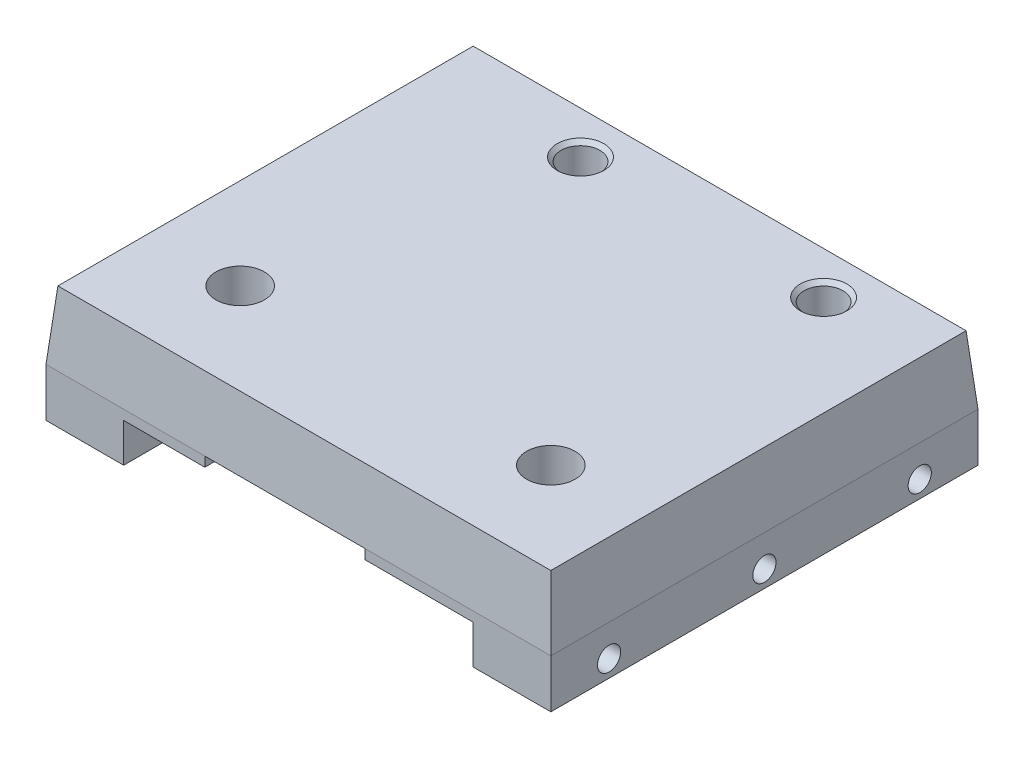
SolidWorks part; units mm, degrees
material "6061 Alloy"
ref_plane "Front Plane" through (0, 0, 0) normal (0, 0, 1) x (1, 0, 0)
ref_plane "Top Plane" through (0, 0, 0) normal (0, 1, 0) x (1, 0, 0)
ref_plane "Right Plane" through (0, 0, 0) normal (1, 0, 0) x (0, 0, -1)
sketch "Sketch1" plane through (0, 0, 0) normal (0, 1, 0) x (1, 0, 0)
  line L1 (41.275, -34.925) -> (-41.275, -34.925)
  line L2 (41.275, -34.925) -> (41.275, 34.925)
  line L3 (41.275, 34.925) -> (-41.275, 34.925)
  line L4 (-41.275, -34.925) -> (-41.275, 34.925)
  line L5 (41.275, -34.925) -> (-41.275, 34.925) construction
  line L6 (41.275, 34.925) -> (-41.275, -34.925) construction
  line L7 (-22.225, 34.925) -> (28.575, 34.925)
  line L8 (-22.225, 34.925) -> (-22.225, 92.075)
  line L9 (-22.225, 92.075) -> (28.575, 92.075)
  line L10 (28.575, 34.925) -> (28.575, 92.075)
  point P0 (0, 0)
  dimension "D1" = 82.55
  dimension "D2" = 69.85
  dimension "D3" = 12.7
  dimension "D4" = 19.05
  dimension "D5" = 50.8
  dimension "D6" = 127
extrude "Boss-Extrude1" add sketch "Sketch1" along normal blind 7.9375 contours L4 L1 L2 L3
sketch "Sketch2" plane through (0, 7.9375, 0) normal (0, 1, 0) x (1, 0, 0)
  line L1 (-41.275, -34.925) -> (41.275, -34.925)
  line L2 (-41.275, -34.925) -> (-41.275, 34.925)
  line L3 (-41.275, 34.925) -> (41.275, 34.925)
  line L4 (41.275, -34.925) -> (41.275, 34.925)
extrude "Boss-Extrude2" add sketch "Sketch2" along normal blind 3.175
hole_wizard "3/8-16 Tapped Hole1" positions "Sketch10" profile "Sketch11" tap size "3/8-16" standard "ANSI Inch"
sketch "Sketch10" plane through (0, 11.1125, 0) normal (0, 1, 0) x (1, 0, 0)
  line L0 (-41.275, 34.925) -> (-41.275, -34.925) construction
  line L1 (-41.275, -34.925) -> (41.275, -34.925) construction
  line L2 (41.275, -34.925) -> (41.275, 34.925) construction
  point P0 (-25.4, -19.05)
  point P2 (25.4, -19.05)
  dimension "D1" = 15.875
  dimension "D2" = 15.875
  dimension "D3" = 15.875
  dimension "D4" = 15.875
sketch "Sketch11" plane through (-25.4, 11.1125, 19.05) normal (1, 0, 0) x (0, 0, 1)
  line L0 (0, 0) -> (0, 11.9097)
  line L1 (0, 11.9097) -> (3.9687, 9.525)
  line L2 (3.9687, 9.525) -> (3.9687, 0)
  line L5 (3.9687, 0) -> (0, 0)
  line L10 (0, 11.9097) -> (-3.9688, 9.525) construction
  line L11 (0, -6.35) -> (0, 107.95) construction
  dimension "Tap Drill Dia." = 7.9375
  dimension "Tap Drill Depth" = 9.525
  dimension "Drill Angle" = 118
cosmetic thread "Hole Thread4" parameters "D1"=19.05, "D2"=9.525
cosmetic thread "Hole Thread5" parameters "D1"=19.05, "D2"=9.525
draft "Draft1" type of draft neutral plane draft angle 5 neutral plane "Top Plane" faces to draft 4 face at (0, 5.5563, -34.925) face at (-41.275, 5.5563, 0) face at (0, 5.5563, 34.925) face at (41.275, 5.5563, 0) neutral plane through (0, 0, 0) neutral plane normal (0, 1, 0) parameters "D1"=5
sketch "Sketch3" plane through (0, 0, 0) normal (0, -1, 0) x (1, 0, 0)
  line L7 (41.275, 34.925) -> (28.575, 34.925)
  line L8 (41.275, 34.925) -> (41.275, -34.925)
  line L9 (41.275, -34.925) -> (28.575, -34.925)
  line L10 (28.575, 34.925) -> (28.575, -34.925)
  line L13 (-41.275, -34.925) -> (-28.575, -34.925)
  line L14 (-41.275, -34.925) -> (-41.275, 34.925)
  line L15 (-41.275, 34.925) -> (-28.575, 34.925)
  line L16 (-28.575, -34.925) -> (-28.575, 34.925)
  dimension "D1" = 12.7
  dimension "D2" = 12.7
extrude "Boss-Extrude3" add sketch "Sketch3" along normal blind 7.9375
sketch "Sketch4" plane through (0, 0, 0) normal (0, -1, 0) x (1, 0, 0)
  line L1 (-28.575, 34.925) -> (-15.3077, 34.925)
  line L2 (-28.575, 34.925) -> (-28.575, -34.925)
  line L3 (-28.575, -34.925) -> (-15.3077, -34.925)
  line L4 (-15.3077, 34.925) -> (-15.3077, -34.925)
  line L6 (28.575, 34.925) -> (10.8909, 34.925)
  line L7 (28.575, 34.925) -> (28.575, -34.925)
  line L8 (28.575, -34.925) -> (10.8909, -34.925)
  line L9 (10.8909, 34.925) -> (10.8909, -34.925)
extrude "Wear Pads" add sketch "Sketch4" along normal blind 1.5875
hole_wizard "#10-24 Tapped Hole1" positions "Sketch5" profile "Sketch6" tap size "#10-24" standard "ANSI Inch"
sketch "Sketch5" plane through (41.275, 0, 0) normal (1, 0, 0) x (0, 0, -1)
  line L6 (-34.925, -5.1516) -> (34.925, -5.1516) construction
  line L8 (-34.925, -7.9375) -> (-34.925, 0) construction
  line L9 (34.925, -7.9375) -> (34.925, 0) construction
  point P0 (-25.4, -5.1516)
  point P2 (25.4, -5.1516)
  point P29 (0, -5.1516)
  dimension "D1" = 9.525
  dimension "D2" = 9.525
sketch "Sketch6" plane through (41.275, -5.1516, 25.4) normal (0, 1, 0) x (0, 0, -1)
  line L0 (0, 0) -> (0, 12.7)
  line L1 (0, 12.7) -> (1.8986, 12.7)
  line L2 (1.8986, 12.7) -> (1.8986, 0)
  line L5 (1.8986, 0) -> (0, 0)
  line L11 (0, -6.35) -> (0, 107.95) construction
  dimension "Thru Tap Drill Dia." = 3.7973
  dimension "Thru Tap Drill Depth" = 12.7
cosmetic thread "Hole Thread1" parameters "D2"=4.826
cosmetic thread "Hole Thread2" parameters "D2"=4.826
cosmetic thread "Hole Thread3" parameters "D2"=4.826
hole_wizard "1/4 (0.25) Diameter Hole1" positions "Sketch16" profile "Sketch17" hole size "1/4" standard "ANSI Inch"
sketch "Sketch16" plane through (0, 11.1125, 0) normal (0, 1, 0) x (1, 0, 0)
  point P0 (-15.8177, 27.0184)
  point P2 (23.9311, 27.0184)
sketch "Sketch17" plane through (-15.8177, 11.1125, -27.0184) normal (1, 0, 0) x (0, 0, 1)
  line L0 (0, 0) -> (0, 10.7977)
  line L1 (0, 10.7977) -> (3.175, 8.89)
  line L2 (3.175, 8.89) -> (3.175, 0.635)
  line L3 (3.175, 0.635) -> (3.81, 0)
  line L5 (3.81, 0) -> (0, 0)
  line L6 (-3.175, 0.635) -> (-3.81, 0) construction
  line L10 (0, 10.7977) -> (-3.175, 8.89) construction
  line L11 (0, -6.35) -> (0, 107.95) construction
  dimension "Hole Dia." = 6.35
  dimension "Hole Depth" = 8.89
  dimension "Near C'Sink Dia." = 7.62
  dimension "Near C'Sink Angle" = 90
  dimension "Drill Angle" = 118
